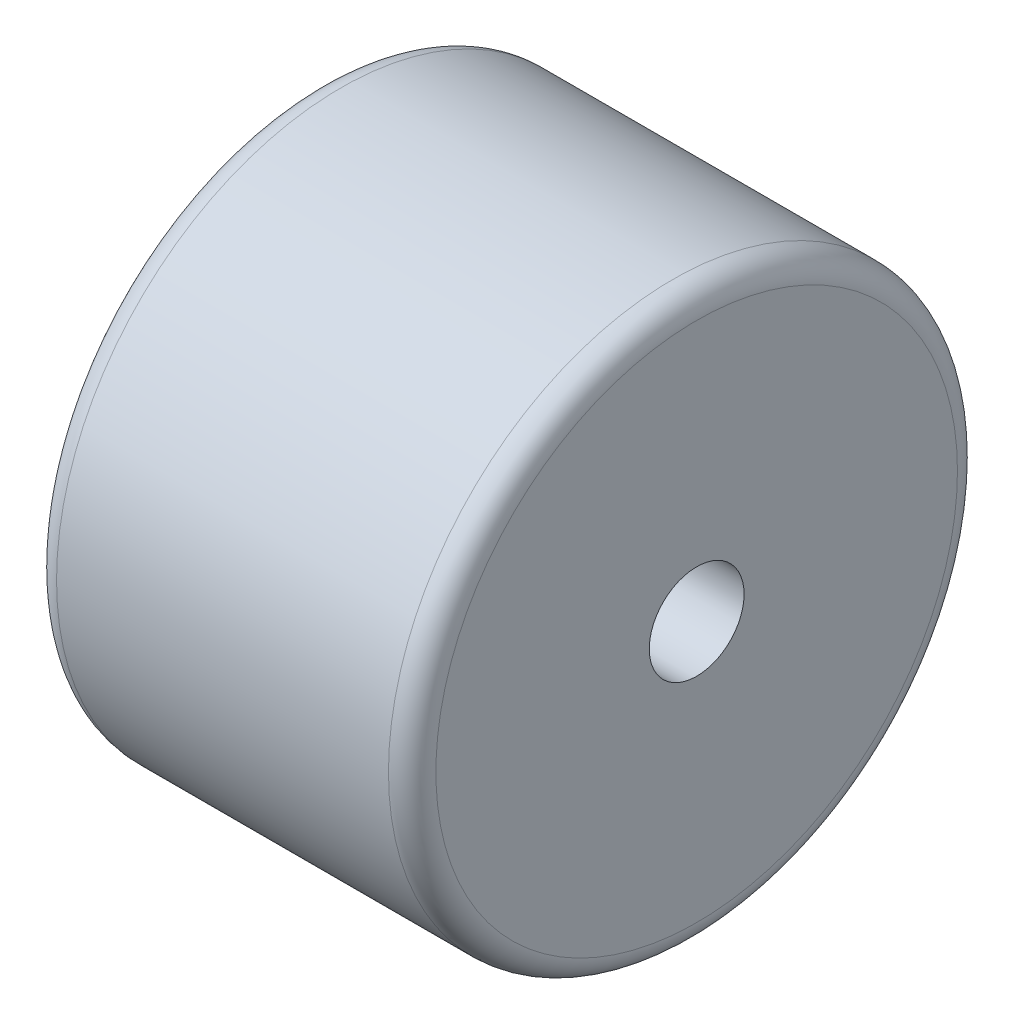
SolidWorks part; units mm, degrees
ref_plane "Front Plane" through (0, 0, 0) normal (0, 0, 1) x (1, 0, 0)
ref_plane "Top Plane" through (0, 0, 0) normal (0, 1, 0) x (1, 0, 0)
ref_plane "Right Plane" through (0, 0, 0) normal (1, 0, 0) x (0, 0, -1)
sketch "Sketch1" plane through (0, 0, 0) normal (1, 0, 0) x (0, 0, -1)
  circle A0 centre (0, 0) radius 9.525
  circle A1 centre (0, 0) radius 1.5875
  dimension "D1" = 19.05
  dimension "D2" = 3.175
extrude "Boss-Extrude1" add sketch "Sketch1" along normal mid plane 12.7
fillet "Fillet1" radius 0.7937 2 edges at (-6.35, 0, -9.525) (6.35, 0, -9.525)
